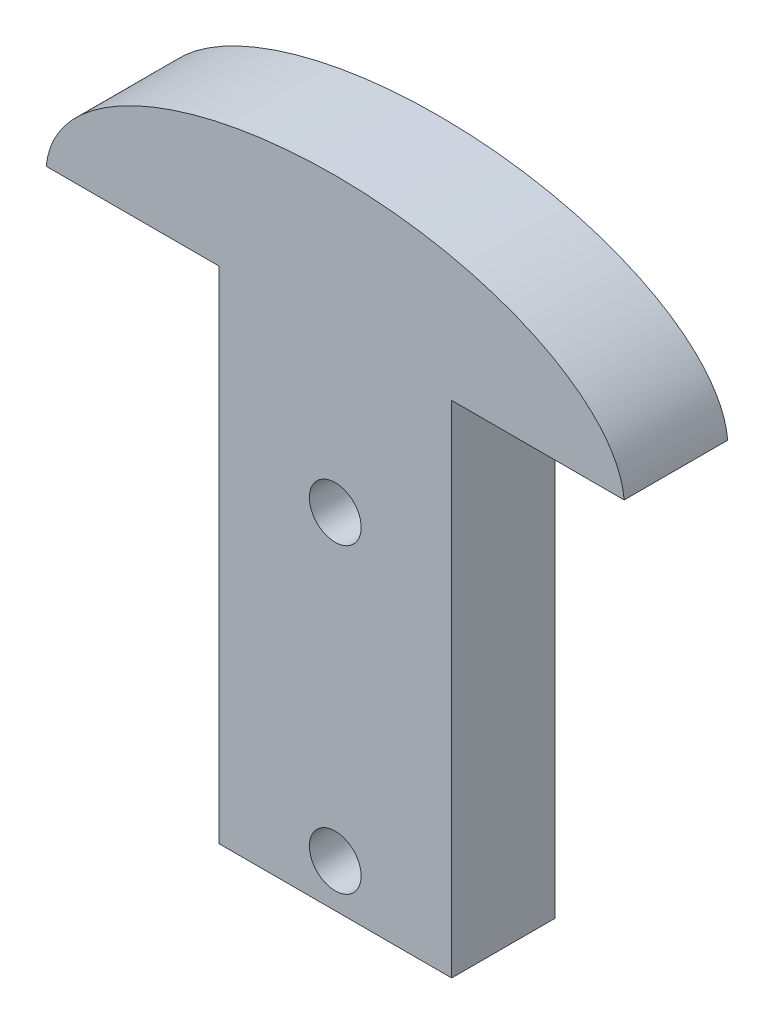
SolidWorks part; units mm, degrees
material "Balsa"
ref_plane "Plano frontal" through (0, 0, 0) normal (0, 0, 1) x (1, 0, 0)
ref_plane "Plano superior" through (0, 0, 0) normal (0, 1, 0) x (1, 0, 0)
ref_plane "Plano direito" through (0, 0, 0) normal (1, 0, 0) x (0, 0, -1)
sketch "Esboço1" plane through (0, 0, 0) normal (0, 0, 1) x (1, 0, 0)
  line L2 (-6.75, 14.75) -> (-6.75, -14.25)
  line L3 (-6.75, -14.25) -> (6.75, -14.25)
  line L4 (6.75, 14.75) -> (6.75, -14.25)
  line L8 (-6.75, 14.75) -> (-16.75, 14.75)
  line L9 (6.75, 14.75) -> (16.75, 14.75)
  circle A0 centre (0, -11.75) radius 1.5
  circle A1 centre (0, 5.75) radius 1.5
  ellipse E1 centre (-0.0002, 14.3993) end of major axis (16.7649, 14.4025) minor radius 8.2685 (16.75, 14.75) -> (-16.75, 14.75) ccw
  point P0 (0, 0)
  point P6 (0, -14.25)
  dimension "D4" = 2.5
  dimension "D5" = 3
  dimension "D6" = 3
  dimension "D1" = 13.5
  dimension "D2" = 29
  dimension "D3" = 10
  dimension "D7" = 10
  dimension "D8" = 20
  dimension "D9" = 29
extrude "Ressalto-extrusão1" add sketch "Esboço1" along normal blind 6
